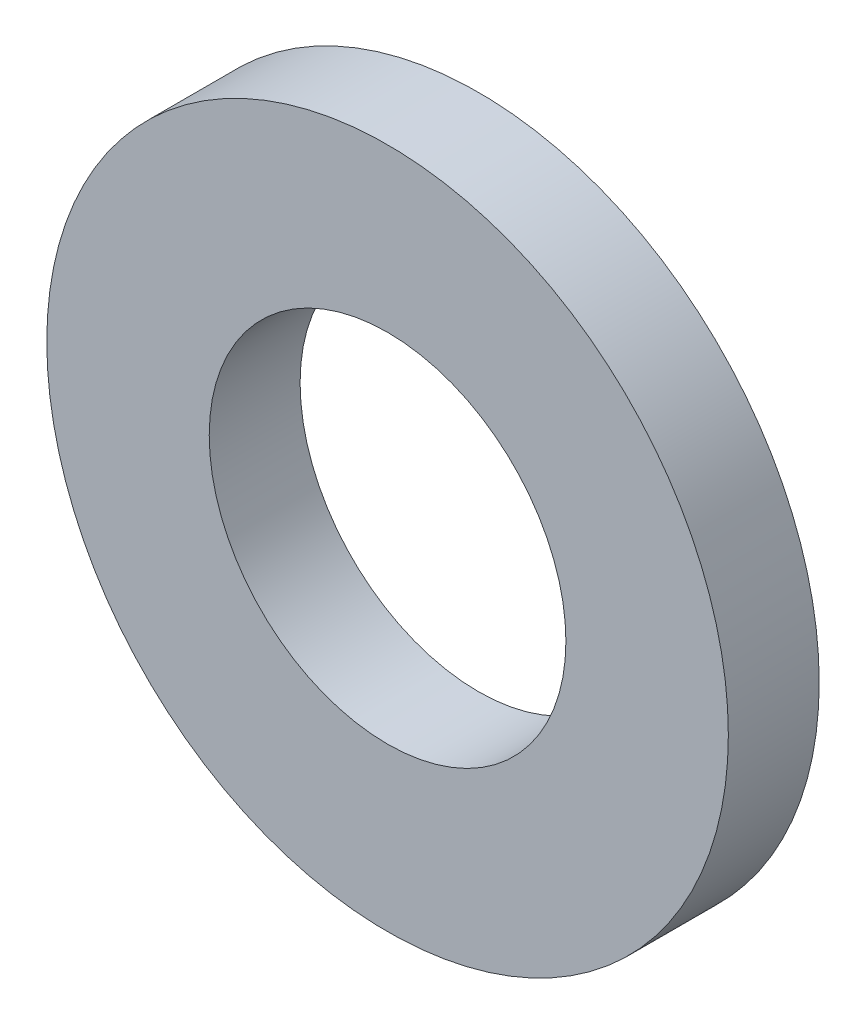
SolidWorks part; units mm, degrees
ref_plane "Front" through (0, 0, 0) normal (0, 0, 1) x (1, 0, 0)
ref_plane "Top" through (0, 0, 0) normal (0, 1, 0) x (1, 0, 0)
ref_plane "Right" through (0, 0, 0) normal (1, 0, 0) x (0, 0, -1)
sketch "Sketch1" plane through (0, 0, 0) normal (0, 0, 1) x (1, 0, 0)
  circle A0 centre (0, 0) radius 1.57
  circle A1 centre (0, 0) radius 3
  dimension "d1" = 3.14
  dimension "d2" = 6
extrude "Base-Extrude" add sketch "Sketch1" against normal blind 0.8
